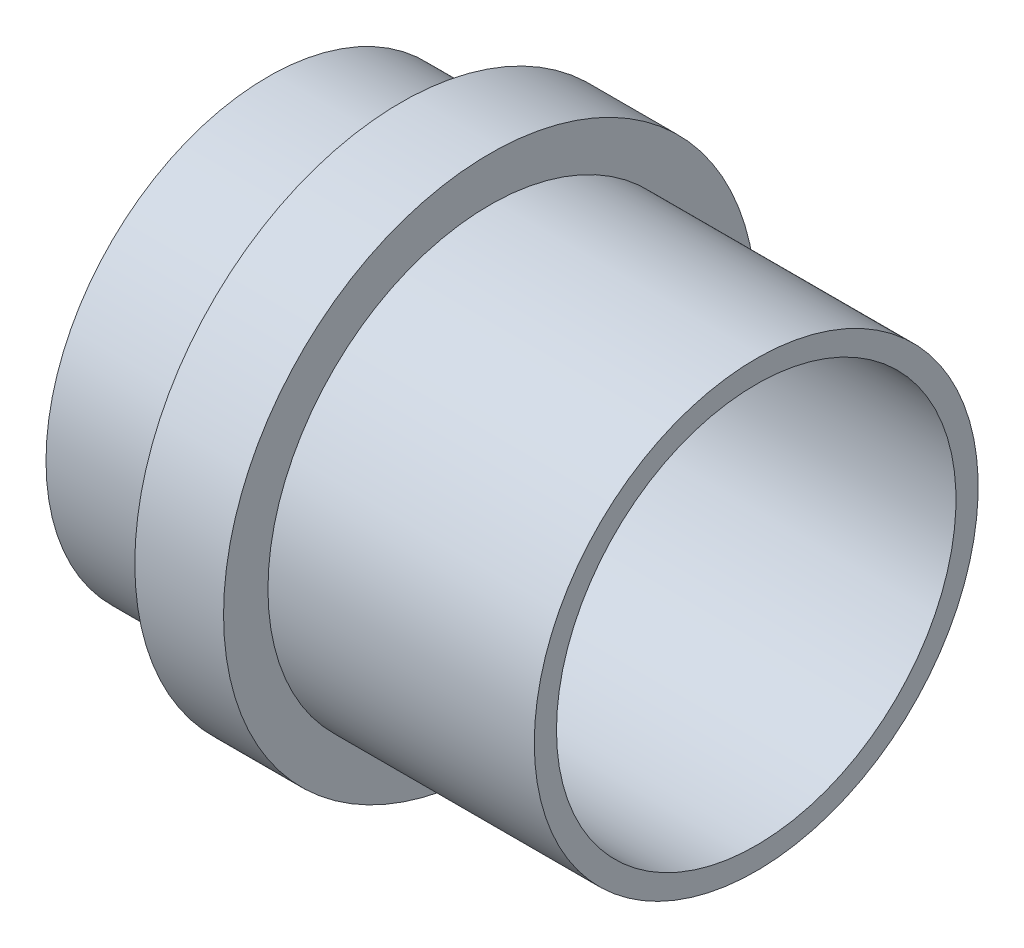
SolidWorks part; units mm, degrees
ref_plane "Front Plane" through (0, 0, 0) normal (0, 0, 1) x (1, 0, 0)
ref_plane "Top Plane" through (0, 0, 0) normal (0, 1, 0) x (1, 0, 0)
ref_plane "Right Plane" through (0, 0, 0) normal (1, 0, 0) x (0, 0, -1)
sketch "Sketch2" plane through (0, 0, 0) normal (0, 0, 1) x (1, 0, 0)
  line L0 (0, 0) -> (139.7, 0)
  line L2 (63.5, 63.5) -> (127, 63.5)
  line L4 (0, 57.15) -> (0, 63.5)
  line L5 (0, 63.5) -> (38.1, 63.5)
  line L8 (38.1, 63.5) -> (38.1, 76.2)
  line L9 (38.1, 76.2) -> (63.5, 76.2)
  line L10 (63.5, 63.5) -> (63.5, 76.2)
  line L11 (38.1, 57.15) -> (0, 57.15)
  line L14 (127, 63.5) -> (139.7, 63.5)
  line L15 (139.7, 57.15) -> (139.7, 63.5)
  line L16 (38.1, 57.15) -> (139.7, 57.15)
  dimension "D1" = 76.2
  dimension "D2" = 12.7
  dimension "D3" = 6.35
  dimension "D4" = 25.4
  dimension "D5" = 38.1
  dimension "D6" = 76.2
revolve "Revolve1" add sketch "Sketch2" angle 360 about L0
